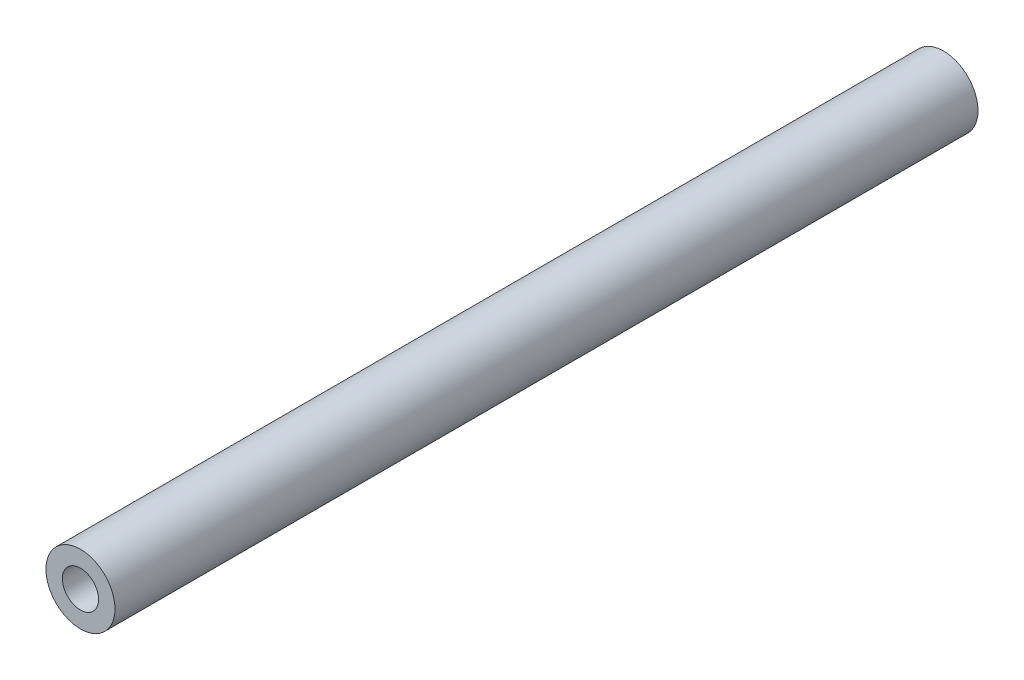
SolidWorks part; units mm, degrees
material "6061 合金"
ref_plane "前视基准面" through (0, 0, 0) normal (0, 0, 1) x (1, 0, 0)
ref_plane "上视基准面" through (0, 0, 0) normal (0, 1, 0) x (1, 0, 0)
ref_plane "右视基准面" through (0, 0, 0) normal (1, 0, 0) x (0, 0, -1)
other "Configuration Table"
sketch "草图1" plane through (0, 0, 0) normal (0, 0, 1) x (1, 0, 0)
  circle A0 centre (0, 0) radius 4
  dimension "D1" = 8
extrude "凸台-拉伸1" add sketch "草图1" along normal mid plane 100
hole_wizard "M5 螺纹孔1" positions "草图2" profile "草图3" tap size "M5" standard "GB"
sketch "草图2" plane through (0, 0, 50) normal (0, 0, 1) x (1, 0, 0)
  point P0 (0, 0)
sketch "草图3" plane through (0, 0, 50) normal (1, 0, 0) x (0, -1, 0)
  line L0 (0, 0) -> (0, 13.6618)
  line L1 (0, 13.6618) -> (2.1, 12.4)
  line L2 (2.1, 12.4) -> (2.1, 0)
  line L5 (2.1, 0) -> (0, 0)
  line L10 (0, 13.6618) -> (-2.1, 12.4) construction
  line L11 (0, -6.35) -> (0, 107.95) construction
  dimension "螺纹孔钻头直径" = 4.2
  dimension "螺纹孔钻头深度" = 12.4
  dimension "导头角度" = 118
cosmetic thread "孔螺蚊线1" parameters "D1"=10, "D2"=5
mirror "镜向1" about plane through (0, 0, 0) normal (0, 0, 1) of "M5 螺纹孔1"
